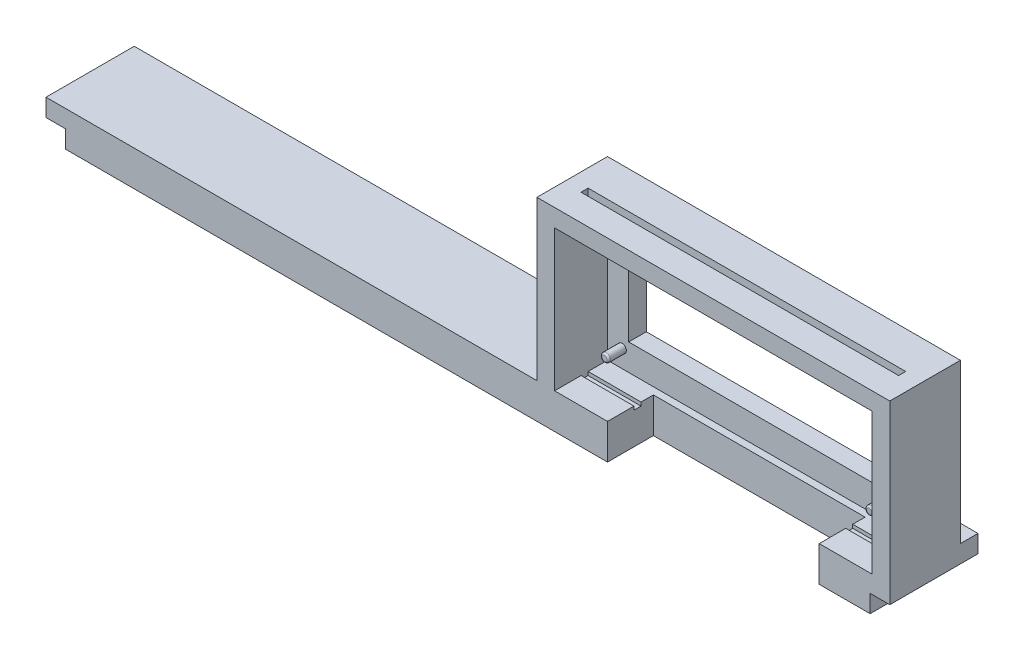
SolidWorks part; units mm, degrees
ref_plane "Front Plane" through (0, 0, 0) normal (0, 0, 1) x (1, 0, 0)
ref_plane "Top Plane" through (0, 0, 0) normal (0, 1, 0) x (1, 0, 0)
ref_plane "Right Plane" through (0, 0, 0) normal (1, 0, 0) x (0, 0, -1)
sketch "Sketch2" plane through (0, 0, 0) normal (0, 0, 1) x (1, 0, 0)
  line L1 (-58.56, 4.1842) -> (41.44, 4.1842)
  line L2 (-58.56, 4.1842) -> (-58.56, -45.8158)
  line L3 (-58.56, -45.8158) -> (41.44, -45.8158)
  line L4 (41.44, 4.1842) -> (41.44, -45.8158)
  dimension "D1" = 50
  dimension "D2" = 100
extrude "Boss-Extrude1" add sketch "Sketch2" along normal blind 20
shell "Shell1" thickness 5
sketch "Sketch3" plane through (0, 0, 20) normal (0, 0, 1) x (1, 0, 0)
  circle A0 centre (-55.774, 1.3816) radius 1.5
ref_plane "Plane1" through (-8.56, 0, 0) normal (-1, 0, 0) x (0, 0, 1)
ref_plane "Plane2" through (0, -20.8158, 0) normal (0, 1, 0) x (1, 0, 0)
sketch "Sketch5" plane through (0, 0, 0) normal (0, 0, -1) x (-1, 0, 0)
  line L0 (-41.44, 4.1842) -> (58.56, 4.1842) construction
  line L1 (-24.44, -8.3158) -> (47.56, -8.3158)
  line L2 (-24.44, -8.3158) -> (-24.44, -33.3158)
  line L3 (-24.44, -33.3158) -> (47.56, -33.3158)
  line L4 (47.56, -8.3158) -> (47.56, -33.3158)
  line L5 (-41.44, -45.8158) -> (-41.44, 4.1842) construction
  dimension "D1" = 25
  dimension "D2" = 72
  dimension "D3" = 12.5
  dimension "D4" = 17
extrude "Cut-Extrude1" cut sketch "Sketch5" against normal through all
sketch "Sketch6" plane through (0, 0, 0) normal (0, 0, -1) x (-1, 0, 0)
  line L0 (11, -20.8158) -> (-11, -20.8158) construction
  line L1 (-24.44, -8.3158) -> (-24.44, -33.3158) construction
  circle A0 centre (-32.94, -20.8158) radius 1.8
  dimension "D1" = 8.5
extrude "Cut-Extrude2" cut sketch "Sketch6" against normal through all contours A0
sketch "Sketch7" plane through (0, 0, 5) normal (0, 0, 1) x (1, 0, 0)
  line L0 (36.44, -40.8158) -> (36.44, -0.8158) construction
  line L1 (29.94, -16.8158) -> (35.94, -16.8158)
  line L2 (29.94, -16.8158) -> (29.94, -24.8158)
  line L3 (29.94, -24.8158) -> (35.94, -24.8158)
  line L4 (35.94, -16.8158) -> (35.94, -24.8158)
  line L5 (11, -20.8158) -> (-11, -20.8158) construction
  dimension "D1" = 8
  dimension "D2" = 0.5
  dimension "D3" = 4
  dimension "D4" = 6
extrude "Cut-Extrude3" cut sketch "Sketch7" against normal blind 4
sketch "Sketch8" plane through (0, -45.8158, 0) normal (0, -1, 0) x (1, 0, 0)
  line L1 (41.44, 20) -> (-197.7, 20)
  line L2 (41.44, 20) -> (41.44, -5)
  line L3 (41.44, -5) -> (-197.7, -5)
  line L4 (-197.7, 20) -> (-197.7, -5)
  dimension "D1" = 25
  dimension "D2" = 239.14
extrude "Boss-Extrude2" add sketch "Sketch8" against normal blind 5
sketch "Sketch9" plane through (0, -45.8158, 0) normal (0, -1, 0) x (1, 0, 0)
  line L0 (41.44, 20) -> (-197.7, 20) construction
  line L1 (-192.13, 20) -> (35.87, 20)
  line L2 (-192.13, 20) -> (-192.13, 1)
  line L3 (-192.13, 1) -> (35.87, 1)
  line L4 (35.87, 20) -> (35.87, 1)
  line L5 (-197.7, 20) -> (-197.7, -5) construction
  dimension "D1" = 19
  dimension "D2" = 228
  dimension "D3" = 0
  dimension "D4" = 5.57
extrude "Boss-Extrude3" add sketch "Sketch9" along normal blind 5
sketch "Sketch10" plane through (0, -40.8158, 0) normal (0, 1, 0) x (1, 0, 0)
  line L0 (21.44, -7) -> (21.44, -20)
  line L1 (21.44, -7) -> (-38.56, -7)
  line L2 (21.44, -20) -> (-38.56, -20)
  line L3 (-38.56, -7) -> (-38.56, -20)
  line L4 (21.44, -7) -> (-38.56, -20) construction
  line L5 (21.44, -20) -> (-38.56, -7) construction
  line L6 (-53.56, -20) -> (36.44, -20) construction
  line L7 (41.44, -20) -> (41.44, 5) construction
  point P1 (-8.56, -13.5)
  dimension "D1" = 13
  dimension "D2" = 60
  dimension "D3" = 0
  dimension "D4" = 30
  dimension "D5" = 20
extrude "Cut-Extrude4" cut sketch "Sketch10" against normal blind 19
sketch "Sketch11" plane through (0, 0, 5) normal (0, 0, 1) x (1, 0, 0)
  line L1 (-53.56, -0.8158) -> (-49.42, -0.8158)
  line L2 (-53.56, -0.8158) -> (-53.56, -4.7758)
  line L3 (-53.56, -4.7758) -> (-49.42, -4.7758)
  line L4 (-49.42, -0.8158) -> (-49.42, -4.7758)
  circle A0 centre (-49.42, -4.7758) radius 1.2
extrude "Boss-Extrude4" add sketch "Sketch11" along normal blind 5 contours A0
sketch "Sketch12" plane through (0, 0, 5) normal (0, 0, 1) x (1, 0, 0)
  line L1 (36.44, -0.8158) -> (25.58, -0.8158)
  line L2 (36.44, -0.8158) -> (36.44, -4.7758)
  line L3 (36.44, -4.7758) -> (25.58, -4.7758)
  line L4 (25.58, -0.8158) -> (25.58, -4.7758)
  circle A0 centre (25.58, -4.7758) radius 1.2
extrude "Boss-Extrude5" add sketch "Sketch12" along normal blind 5 contours A0
sketch "Sketch13" plane through (0, 0, 5) normal (0, 0, 1) x (1, 0, 0)
  line L1 (-53.56, -40.8158) -> (-49.42, -40.8158)
  line L2 (-53.56, -40.8158) -> (-53.56, -35.7758)
  line L3 (-53.56, -35.7758) -> (-49.42, -35.7758)
  line L4 (-49.42, -40.8158) -> (-49.42, -35.7758)
  circle A0 centre (-49.42, -35.7758) radius 1.2
extrude "Boss-Extrude6" add sketch "Sketch13" along normal blind 5 contours A0
sketch "Sketch14" plane through (0, 0, 5) normal (0, 0, 1) x (1, 0, 0)
  line L1 (36.44, -40.8158) -> (25.58, -40.8158)
  line L2 (36.44, -40.8158) -> (36.44, -35.7758)
  line L3 (36.44, -35.7758) -> (25.58, -35.7758)
  line L4 (25.58, -40.8158) -> (25.58, -35.7758)
  circle A0 centre (25.58, -35.7758) radius 1.2
extrude "Boss-Extrude7" add sketch "Sketch14" along normal blind 5 contours A0
fillet "Fillet3" radius 0.5 1 edges at (-48.22, -35.7758, 10)
fillet "Fillet4" radius 0.5 1 edges at (-48.22, -4.7758, 10)
fillet "Fillet5" radius 0.5 1 edges at (26.78, -4.7758, 10)
fillet "Fillet6" radius 0.5 1 edges at (26.78, -35.7758, 10)
sketch "Sketch16" plane through (0, -40.8158, 0) normal (0, 1, 0) x (1, 0, 0)
  line L2 (-53.56, -20) -> (-53.56, -5) construction
  line L3 (-53.56, -10.5) -> (-38.56, -10.5)
  line L4 (-53.56, -10.5) -> (-53.56, -12.5)
  line L5 (-53.56, -12.5) -> (-38.56, -12.5)
  line L6 (-38.56, -10.5) -> (-38.56, -12.5)
  line L7 (-38.56, -7) -> (-38.56, -20) construction
  line L9 (21.44, -20) -> (21.44, -7) construction
  line L10 (21.44, -10.5) -> (36.44, -10.5)
  line L11 (21.44, -10.5) -> (21.44, -12.5)
  line L12 (21.44, -12.5) -> (36.44, -12.5)
  line L13 (36.44, -10.5) -> (36.44, -12.5)
  line L14 (36.44, -20) -> (36.44, -5) construction
extrude "Cut-Extrude5" cut sketch "Sketch16" against normal blind 1
sketch "Sketch17" plane through (0, -0.8158, 0) normal (0, -1, 0) x (1, 0, 0)
  line L3 (-53.56, 20) -> (-53.56, 5) construction
  line L4 (-53.56, 10.5) -> (36.44, 10.5)
  line L5 (-53.56, 10.5) -> (-53.56, 12.5)
  line L6 (-53.56, 12.5) -> (36.44, 12.5)
  line L7 (36.44, 10.5) -> (36.44, 12.5)
  line L8 (36.44, 20) -> (36.44, 5) construction
extrude "Cut-Extrude6" cut sketch "Sketch17" against normal through all
